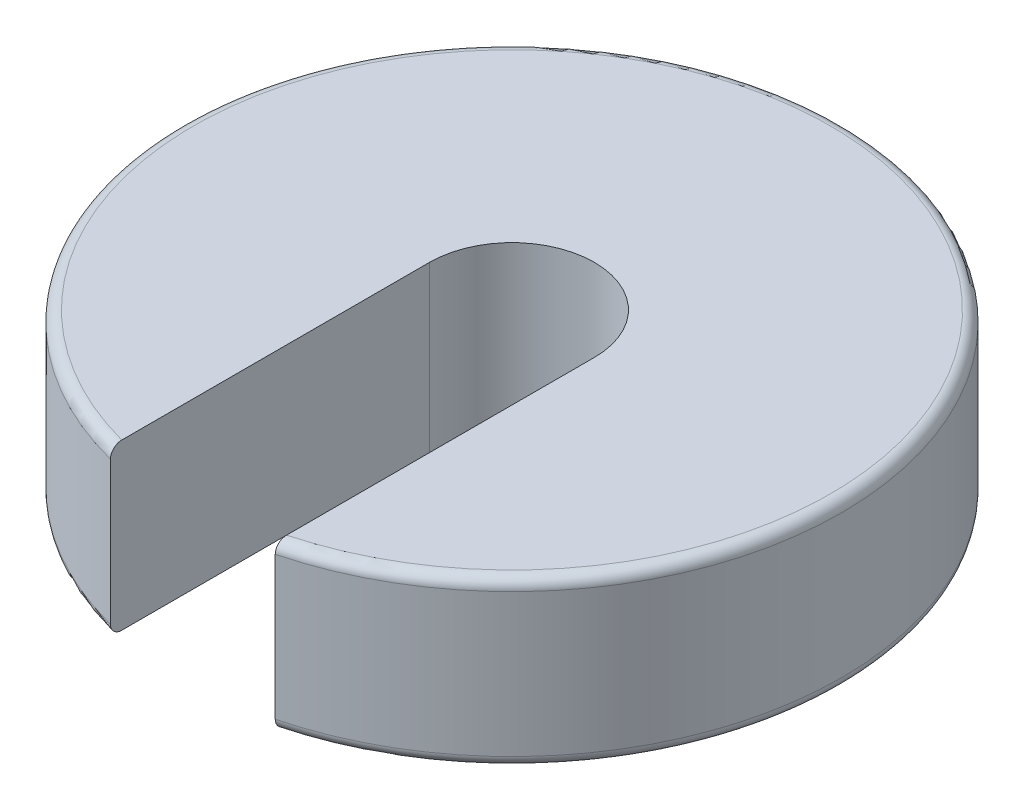
SolidWorks part; units mm, degrees
ref_plane "Front Plane" through (0, 0, 0) normal (0, 0, 1) x (1, 0, 0)
ref_plane "Top Plane" through (0, 0, 0) normal (0, 1, 0) x (1, 0, 0)
ref_plane "Right Plane" through (0, 0, 0) normal (1, 0, 0) x (0, 0, -1)
sketch "Sketch1" plane through (0, 0, 0) normal (0, 1, 0) x (1, 0, 0)
  line L0 (-1.5, 0) -> (-1.5, -5.8095)
  line L1 (1.5, 0) -> (1.5, -5.8095)
  arc A0 (1.5, 0) -> (-1.5, 0) centre (0, 0) ccw
  arc A1 (1.5, -5.8095) -> (-1.5, -5.8095) centre (0, 0) ccw
  dimension "D1" = 12
  dimension "D2" = 3
extrude "Boss-Extrude1" add sketch "Sketch1" along normal blind 3
fillet "Fillet1" radius 0.2 2 edges at (0, 0, -6) (0, 3, -6)
